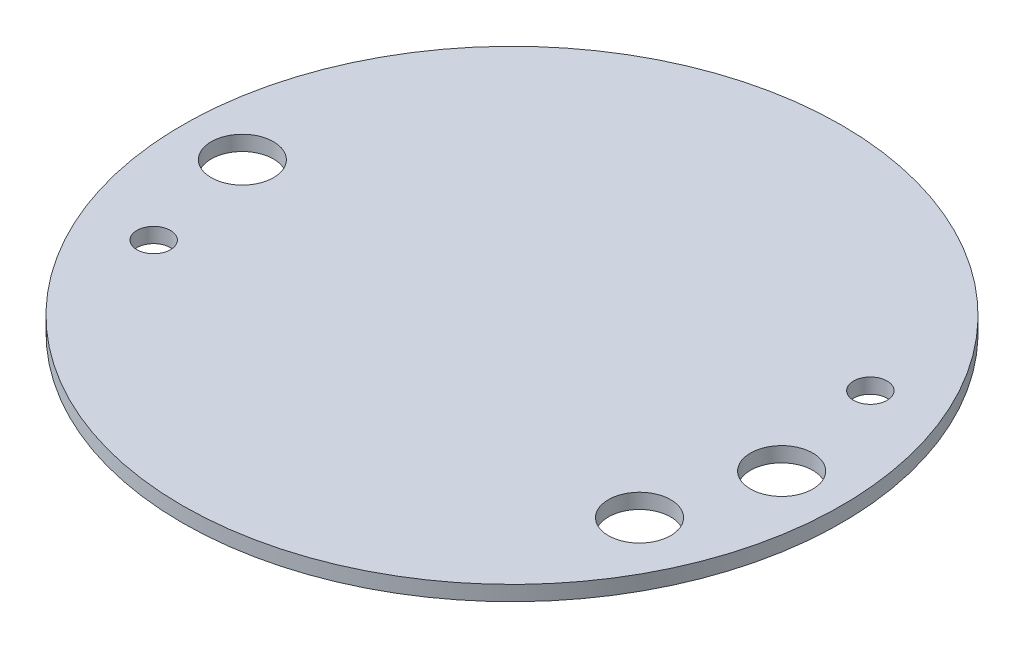
SolidWorks part; units mm, degrees
ref_plane "Front Plane" through (0, 0, 0) normal (0, 0, 1) x (1, 0, 0)
ref_plane "Top Plane" through (0, 0, 0) normal (0, 1, 0) x (1, 0, 0)
ref_plane "Right Plane" through (0, 0, 0) normal (1, 0, 0) x (0, 0, -1)
sketch "Sketch1" plane through (0, 0, 0) normal (0, 1, 0) x (1, 0, 0)
  circle A0 centre (0, 0) radius 69.85
extrude "Boss-Extrude1" add sketch "Sketch1" along normal blind 3.175
sketch "Sketch2" plane through (0, 3.175, 0) normal (0, 1, 0) x (1, 0, 0)
  line L0 (57.15, 0) -> (-57.15, 0) construction
  line L1 (51.7955, 24.1526) -> (-51.7955, -24.1526)
  line L2 (0, 0) -> (50.6445, -23.6159) construction
  circle A0 centre (-57.15, 0) radius 6.604
  circle A1 centre (57.15, 0) radius 6.604
  circle A2 centre (-51.7955, -24.1526) radius 3.556
  circle A3 centre (51.7955, 24.1526) radius 3.556
  circle A4 centre (50.6445, -23.6159) radius 6.604
  point P4 (0, 0)
  point P10 (0, 0)
extrude "Cut-Extrude1" cut sketch "Sketch2" against normal blind 3.175
